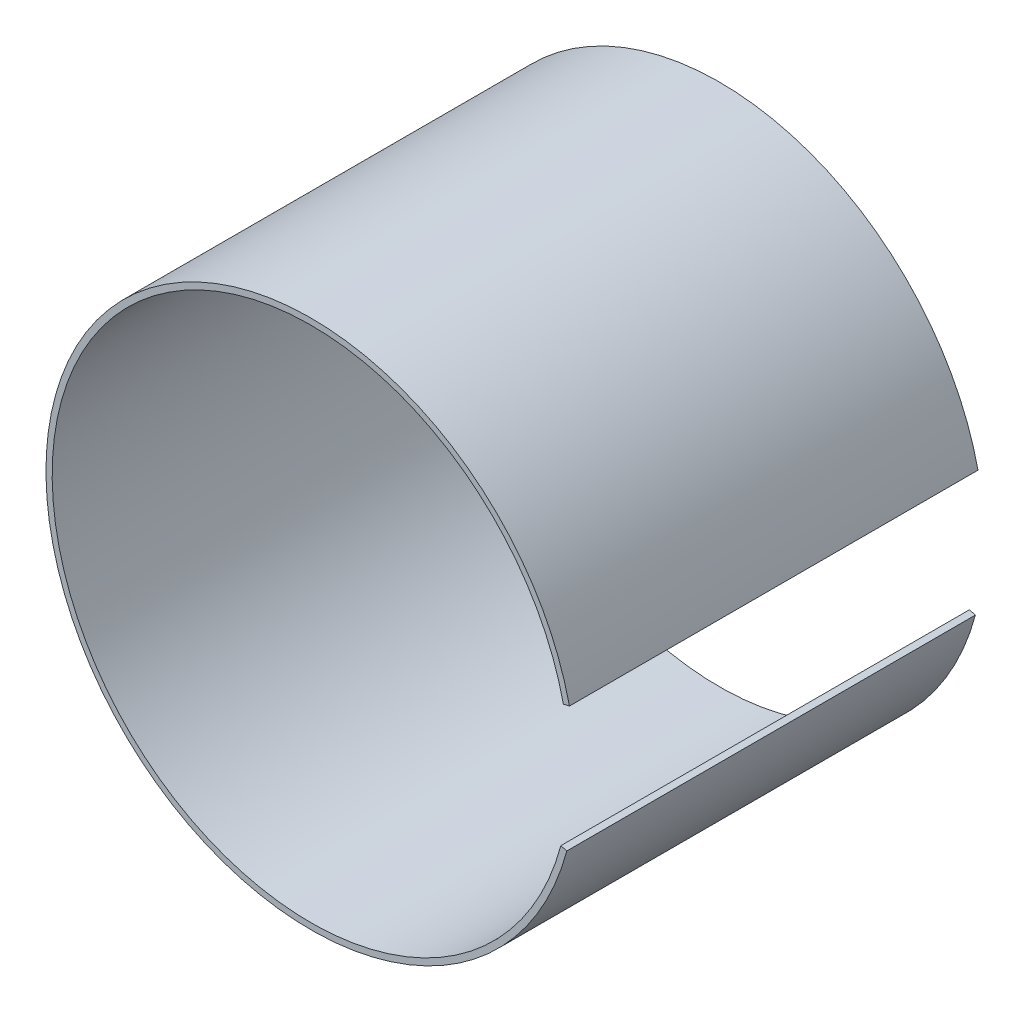
SolidWorks part; units mm, degrees
ref_plane "Front Plane" through (0, 0, 0) normal (0, 0, 1) x (1, 0, 0)
ref_plane "Top Plane" through (0, 0, 0) normal (0, 1, 0) x (1, 0, 0)
ref_plane "Right Plane" through (0, 0, 0) normal (1, 0, 0) x (0, 0, -1)
sketch "Sketch1" plane through (0, 0, 0) normal (0, 0, 1) x (1, 0, 0)
  line L0 (0, -55) -> (0, 55) construction
  line L1 (55, 0) -> (-55, 0) construction
  arc A0 (20.3911, 4.5842) -> (20.1861, -5.4158) centre (0, 0) ccw
  dimension "D1" = 10
  dimension "D2" = 20.9
extrude "Extrude-Thin1" add sketch "Sketch1" along normal blind 33 thin
